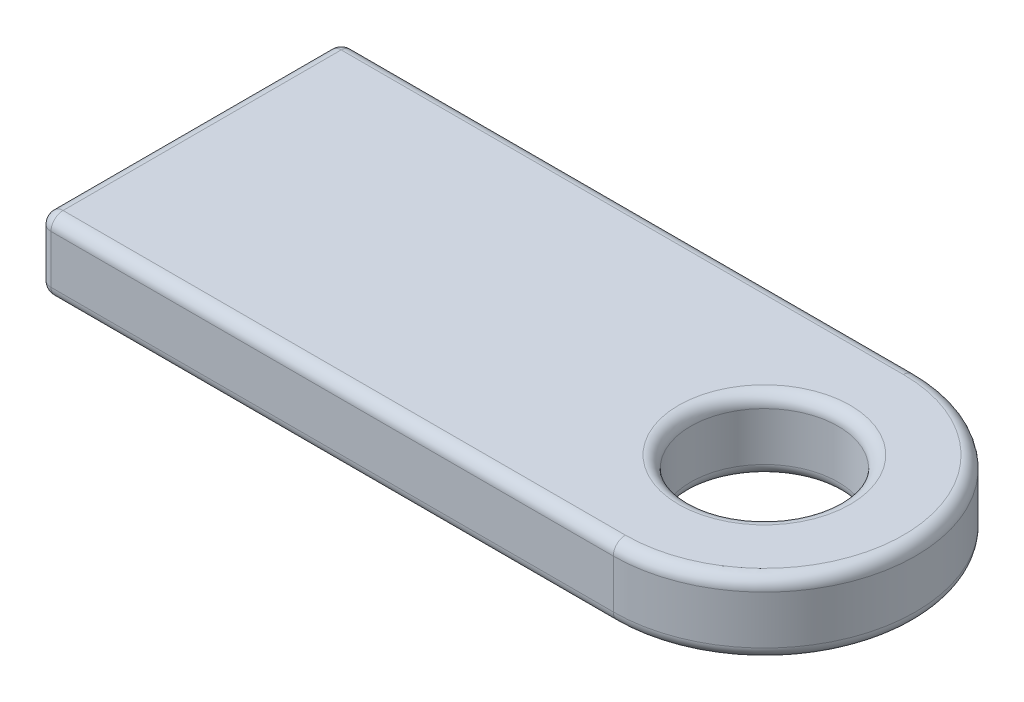
SolidWorks part; units mm, degrees
ref_plane "前视基准面" through (0, 0, 0) normal (0, 0, 1) x (1, 0, 0)
ref_plane "上视基准面" through (0, 0, 0) normal (0, 1, 0) x (1, 0, 0)
ref_plane "右视基准面" through (0, 0, 0) normal (1, 0, 0) x (0, 0, -1)
sketch "草图1" plane through (0, 0, 0) normal (0, 1, 0) x (1, 0, 0)
  line L1 (0, 0) -> (23.75, 0)
  line L2 (0, 0) -> (0, 12.5)
  line L3 (0, 12.5) -> (23.75, 12.5)
  arc A0 (23.75, 0) -> (23.75, 12.5) centre (23.75, 6.25) ccw
  circle A1 centre (23.75, 6.25) radius 3.05
  dimension "D1" = 6.1
extrude "凸台-拉伸1" add sketch "草图1" along normal blind 3
fillet "圆角1" radius 0.5 12 edges at (23.75, 0, -3.2) (11.875, 0, 0) (30, 0, -6.25) (11.875, 0, -12.5) (0, 0, -6.25) (23.75, 3, -3.2) (11.875, 3, -12.5) (30, 3, -6.25) (11.875, 3, 0) (0, 3, -6.25) (0, 1.5, 0) (0, 1.5, -12.5)
